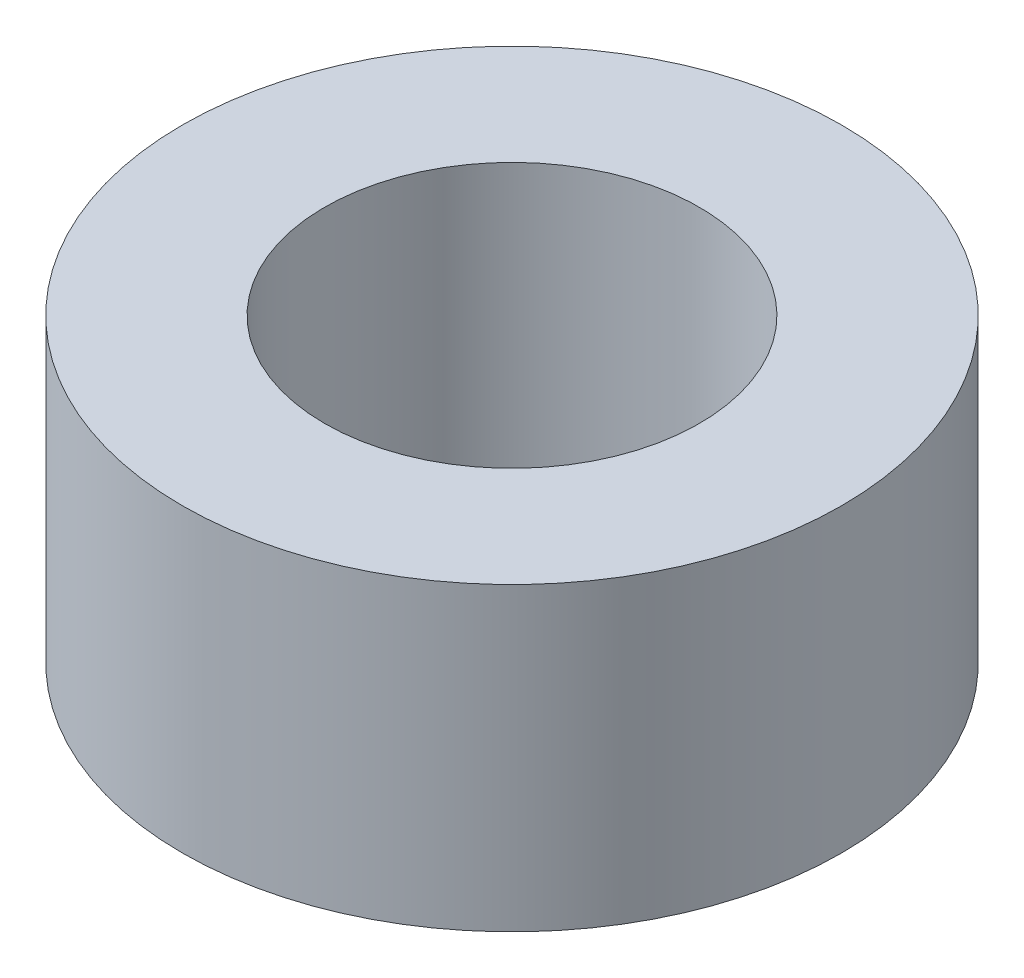
SolidWorks part; units mm, degrees
ref_plane "Front" through (0, 0, 0) normal (0, 0, 1) x (1, 0, 0)
ref_plane "Top" through (0, 0, 0) normal (0, 1, 0) x (1, 0, 0)
ref_plane "Right" through (0, 0, 0) normal (1, 0, 0) x (0, 0, -1)
sketch "Sketch1" plane through (0, 0, 0) normal (0, 1, 0) x (1, 0, 0)
  circle A0 centre (0, 0) radius 3.125
  circle A2 centre (0, 0) radius 5.4991
  dimension "D1" = 6.25
  dimension "D3" = 10.9982
extrude "Boss-Extrude1" add sketch "Sketch1" along normal blind 5.0165
ref_plane "Plane1" through (0, 2.5082, 0) normal (0, 1, 0) x (1, 0, 0)
sketch "Sketch2" plane through (0, 2.5082, 0) normal (0, 1, 0) x (1, 0, 0)
  line L1 (0, 6.0283) -> (0, -5.9658) construction
  point P3 (0, 0)
ref_plane "Plane2" through (0, 2.5082, 0) normal (0, 0, 1) x (1, 0, 0)
sketch "Sketch3" plane through (0, 2.5082, 0) normal (0, 0, 1) x (1, 0, 0)
  line L0 (0, -6.5571) -> (0, 6.5231) construction
ref_plane "Plane3" through (0, 0, 0) normal (-1, 0, 0) x (0, 0, 1)
